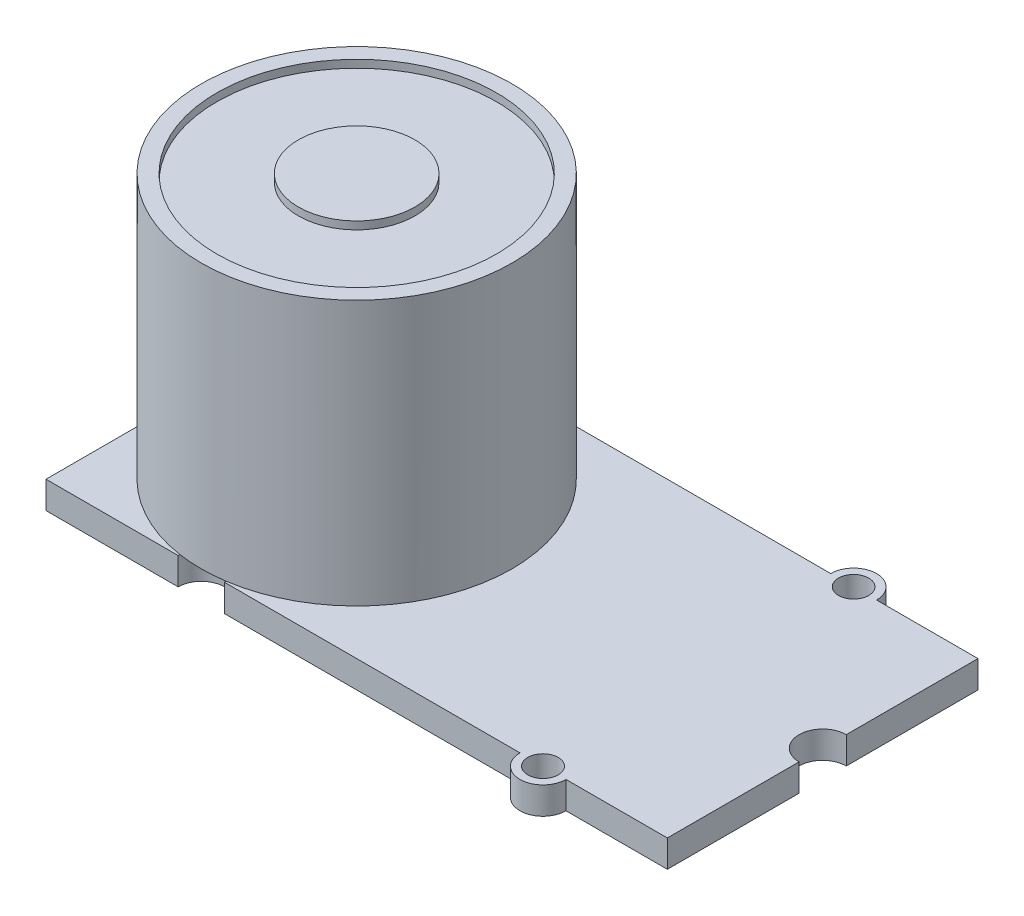
SolidWorks part; units mm, degrees
ref_plane "Front Plane" through (0, 0, 0) normal (0, 0, 1) x (1, 0, 0)
ref_plane "Top Plane" through (0, 0, 0) normal (0, 1, 0) x (1, 0, 0)
ref_plane "Right Plane" through (0, 0, 0) normal (1, 0, 0) x (0, 0, -1)
sketch "Sketch1" plane through (0, 0, 0) normal (0, 1, 0) x (1, 0, 0)
  line L1 (-20, -10) -> (20, -10)
  line L2 (-20, -10) -> (-20, 10)
  line L3 (-20, 10) -> (20, 10)
  line L4 (20, -10) -> (20, 10)
  line L5 (-20, -10) -> (20, 10) construction
  line L6 (-20, 10) -> (20, -10) construction
  point P0 (0, 0)
  dimension "D1" = 20
  dimension "D2" = 40
sketch "Sketch2" plane through (0, 0, 0) normal (0, 1, 0) x (1, 0, 0)
  line L0 (-20, 0) -> (0, 0) construction
  line L1 (-20, -10) -> (-20, 10) construction
  line L2 (0, 0) -> (20, 0) construction
  line L3 (20, -10) -> (20, 10) construction
  circle A0 centre (-10, 0) radius 10
extrude "Boss-Extrude1" add sketch "Sketch1" along normal blind 1.75
extrude "Boss-Extrude2" add sketch "Sketch2" along normal blind 18.8
sketch "Sketch3" plane through (0, 18.8, 0) normal (0, 1, 0) x (1, 0, 0)
  line L0 (-20, 0) -> (0, 0) construction
  line L1 (-20, 0) -> (-20, -10) construction
  circle A0 centre (-10, 0) radius 10 construction
  circle A1 centre (-10, 0) radius 3.75
  circle A2 centre (-10, 0) radius 8.9989
  dimension "D1" = 7.5
extrude "Cut-Extrude2" cut sketch "Sketch3" against normal blind 0.5 contours A2 | A1
sketch "Sketch4" plane through (0, 1.75, 0) normal (0, 1, 0) x (1, 0, 0)
  line L0 (20, -10) -> (20, 10) construction
  circle A0 centre (20, 0) radius 1.5195
extrude "Cut-Extrude3" cut sketch "Sketch4" against normal through all
sketch "Sketch5" plane through (0, 0, 0) normal (0, -1, 0) x (1, 0, 0)
  line L0 (0, 0) -> (-20, 0) construction
  line L1 (-20, -10) -> (-20, 10) construction
  line L2 (-10, 0) -> (-10, 10) construction
  line L3 (-10, 10) -> (-10, -10) construction
  circle A0 centre (-10, 10) radius 1.4945
  circle A1 centre (-10, -10) radius 1.5441
extrude "Cut-Extrude5" cut sketch "Sketch5" against normal up to surface (1.75 mm away) up to face at (11.4134, 1.75, 0)
sketch "Sketch7" plane through (0, 1.75, 0) normal (0, 1, 0) x (1, 0, 0)
  line L0 (11.994, 10) -> (11.994, -10) construction
  line L1 (20, 10) -> (-8.4559, 10) construction
  line L2 (-8.5055, -10) -> (20, -10) construction
  circle A0 centre (11.994, -10) radius 1.4822
  circle A1 centre (11.994, 10) radius 1.4761
extrude "Boss-Extrude3" add sketch "Sketch7" against normal up to surface (1.75 mm away) up to face at (-0.152, 0, 0.005)
sketch "Sketch8" plane through (0, 1.75, 0) normal (0, 1, 0) x (1, 0, 0)
  circle A0 centre (11.994, 10) radius 0.9729
  circle A1 centre (11.994, -10) radius 0.9784
extrude "Cut-Extrude6" cut sketch "Sketch8" against normal through all
